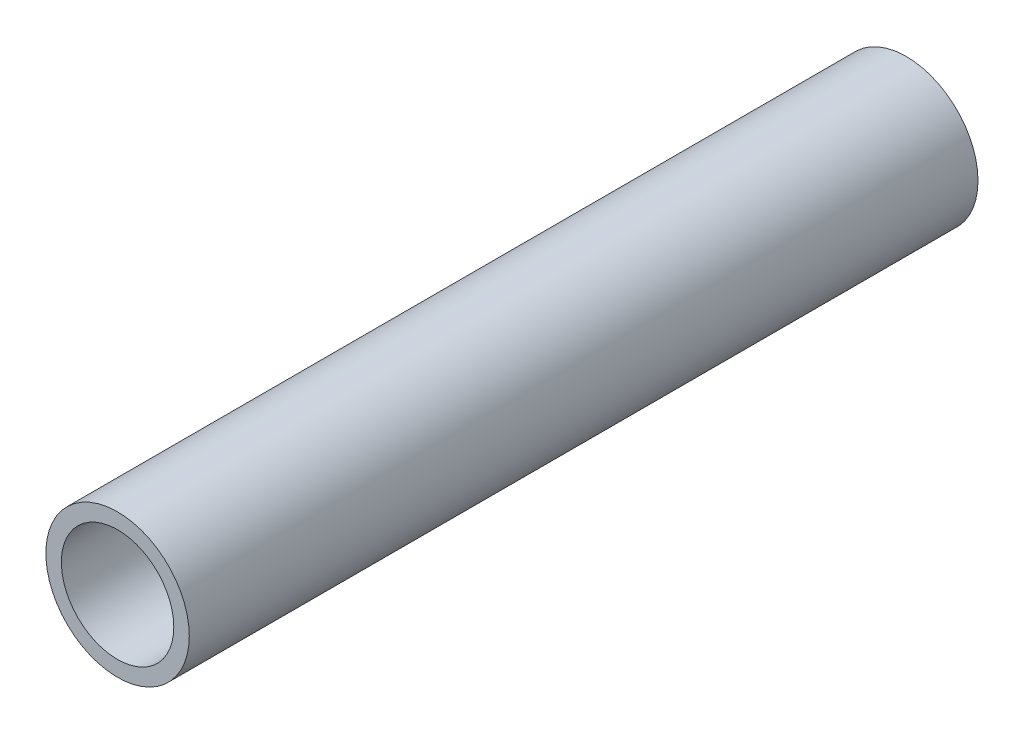
SolidWorks part; units mm, degrees
material "6061-T6 (SS)"
ref_plane "Front Plane" through (0, 0, 0) normal (0, 0, 1) x (1, 0, 0)
ref_plane "Top Plane" through (0, 0, 0) normal (0, 1, 0) x (1, 0, 0)
ref_plane "Right Plane" through (0, 0, 0) normal (1, 0, 0) x (0, 0, -1)
sketch "Sketch1" plane through (0, 0, 0) normal (0, 0, 1) x (1, 0, 0)
  circle A0 centre (0, 0) radius 3.175
  circle A1 centre (0, 0) radius 2.4892
  dimension "D1" = 6.35
  dimension "D2" = 4.9784
extrude "Boss-Extrude1" add sketch "Sketch1" along normal blind 34.925
